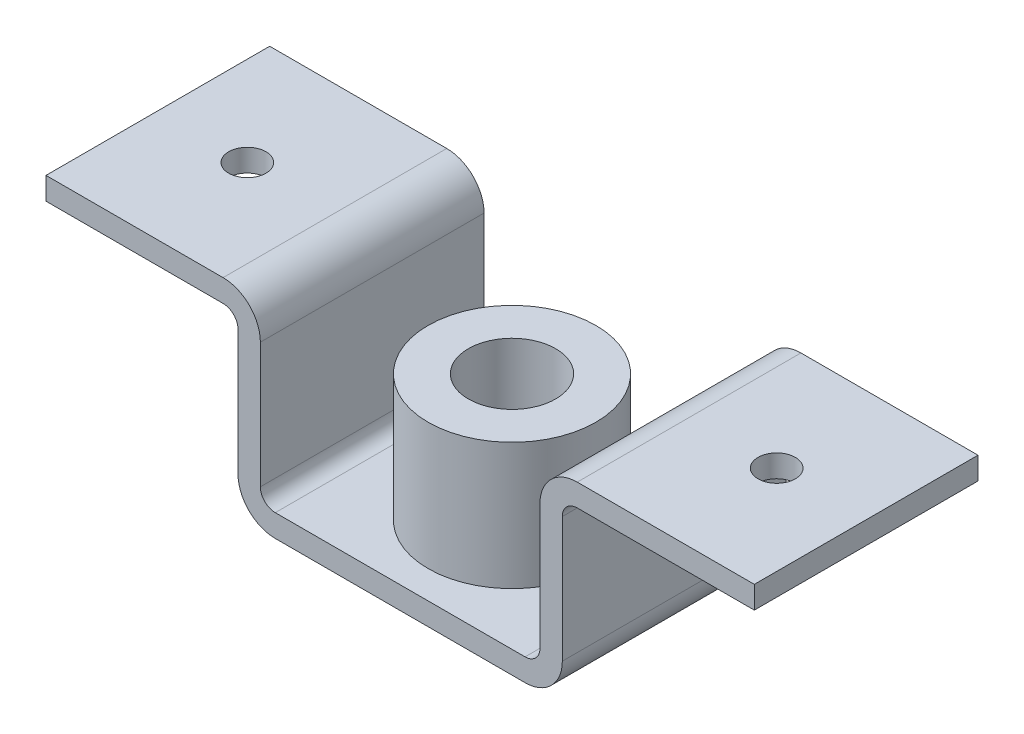
SolidWorks part; units mm, degrees
ref_plane "Front Plane" through (0, 0, 0) normal (0, 0, 1) x (1, 0, 0)
ref_plane "Top Plane" through (0, 0, 0) normal (0, 1, 0) x (1, 0, 0)
ref_plane "Right Plane" through (0, 0, 0) normal (1, 0, 0) x (0, 0, -1)
sketch "Sketch1" plane through (0, 0, 0) normal (0, 0, 1) x (1, 0, 0)
  line L0 (-187.5, 0) -> (187.5, 0)
  line L1 (-187.5, 0) -> (-187.5, 238)
  line L2 (-187.5, 238) -> (-475, 238)
  line L3 (-217.5, -30) -> (217.5, -30)
  line L4 (-217.5, -30) -> (-217.5, 208)
  line L5 (-217.5, 208) -> (-475, 208)
  line L6 (0, 0) -> (0, -30) construction
  line L7 (-187.5, 0) -> (187.5, 0) construction
  line L8 (-217.5, -30) -> (187.5, -30) construction
  line L9 (217.5, -30) -> (217.5, 208)
  line L10 (187.5, 0) -> (187.5, 238)
  line L11 (217.5, 208) -> (475, 208)
  line L12 (187.5, 238) -> (475, 238)
  line L13 (-475, 238) -> (-475, 208)
  line L14 (475, 238) -> (475, 208)
  point P15 (-187.5, 119)
  dimension "D1" = 375
  dimension "D2" = 30
  dimension "D3" = 238
  dimension "D4" = 475
  dimension "D5" = 30
extrude "Boss-Extrude1" add sketch "Sketch1" along normal mid plane 300
fillet "Fillet1" radius 20 4 edges at (217.5, 208, 0) (187.5, 0, 0) (-217.5, 208, 0) (-187.5, 0, 0)
fillet "Fillet2" radius 50 4 edges at (187.5, 238, 0) (-187.5, 238, 0) (-217.5, -30, 0) (217.5, -30, 0)
sketch "Sketch2" plane through (0, 238, 0) normal (0, 1, 0) x (1, 0, 0)
  line L0 (0, 0) -> (0, 180.8201) construction
  line L1 (-475, -150) -> (-475, 150) construction
  line L2 (-237.5, -150) -> (-475, -150) construction
  circle A0 centre (-355, 0) radius 25
  circle A2 centre (355, 0) radius 25
  dimension "D1" = 50
  dimension "D2" = 120
  dimension "D3" = 150
extrude "Cut-Extrude1" cut sketch "Sketch2" against normal through all
sketch "Sketch3" plane through (0, 0, 0) normal (0, 1, 0) x (1, 0, 0)
  circle A0 centre (0, 0) radius 112.5
  circle A1 centre (0, 0) radius 58.5
  dimension "D1" = 225
  dimension "D2" = 117
extrude "Boss-Extrude2" add sketch "Sketch3" along normal blind 170
